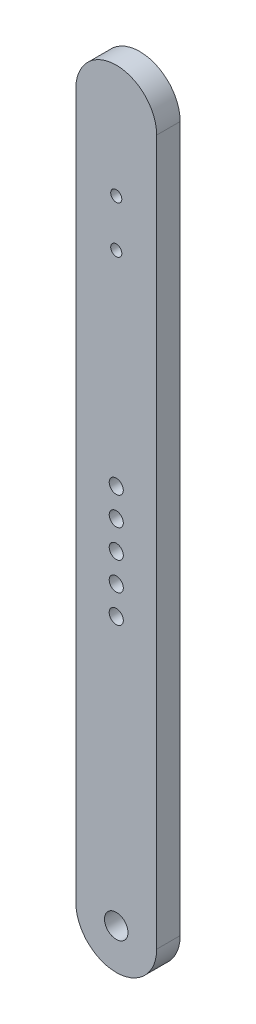
SolidWorks part; units mm, degrees
ref_plane "Front Plane" through (0, 0, 0) normal (0, 0, 1) x (1, 0, 0)
ref_plane "Top Plane" through (0, 0, 0) normal (0, 1, 0) x (1, 0, 0)
ref_plane "Right Plane" through (0, 0, 0) normal (1, 0, 0) x (0, 0, -1)
sketch "Sketch1" plane through (0, 0, 0) normal (0, 0, 1) x (1, 0, 0)
  line L0 (0, 0) -> (0, 190.5) construction
  line L1 (-10.922, 0) -> (-10.922, 190.5)
  line L2 (10.922, 0) -> (10.922, 190.5)
  arc A0 (-10.922, 0) -> (10.922, 0) centre (0, 0) ccw
  arc A1 (10.922, 190.5) -> (-10.922, 190.5) centre (0, 190.5) ccw
  circle A2 centre (0, 0) radius 3.175
  circle A3 centre (0, 95.25) radius 1.905
  circle A4 centre (0, 87.63) radius 1.905
  circle A5 centre (0, 80.01) radius 1.905
  circle A6 centre (0, 72.39) radius 1.905
  circle A7 centre (0, 102.87) radius 1.905
  circle A8 centre (0, 170.7892) radius 1.4999
  circle A9 centre (0, 158.0892) radius 1.4999
  point P3 (0, 95.25)
  dimension "D3" = 6.35
  dimension "D4" = 3.81
  dimension "D5" = 7.62
  dimension "D6" = 3.81
  dimension "D9" = 3.81
  dimension "D10" = 3.81
  dimension "D11" = 7.62
  dimension "D12" = 3.81
  dimension "D13" = 2.9997
  dimension "D14" = 2.9997
  dimension "D1" = 190.5
  dimension "D2" = 10.922
  dimension "D7" = 7.62
  dimension "D8" = 7.62
  dimension "D15" = 12.7
  dimension "D16" = 19.7108
extrude "Boss-Extrude1" add sketch "Sketch1" along normal blind 6.35
